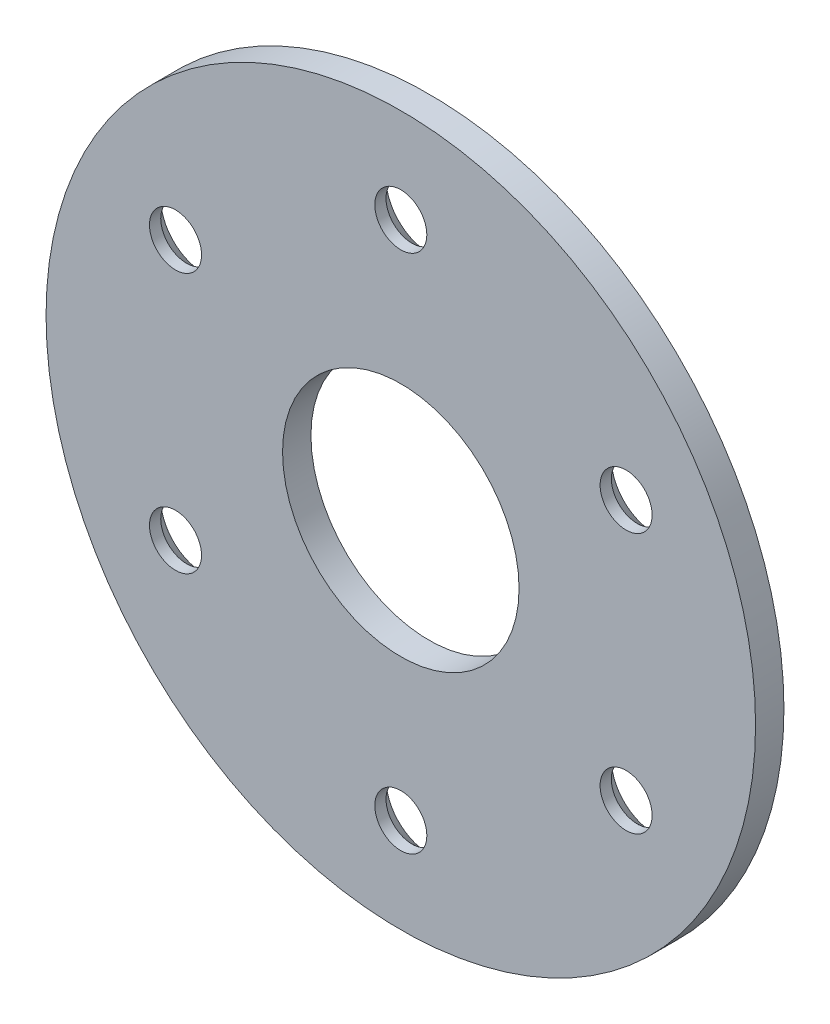
SolidWorks part; units mm, degrees
material "AISI 304"
ref_plane "Спереди" through (0, 0, 0) normal (0, 0, 1) x (1, 0, 0)
ref_plane "Сверху" through (0, 0, 0) normal (0, 1, 0) x (1, 0, 0)
ref_plane "Справа" through (0, 0, 0) normal (1, 0, 0) x (0, 0, -1)
sketch "Эскиз1" plane through (0, 0, 0) normal (0, 0, 1) x (1, 0, 0)
  circle A0 centre (0, 0) radius 75
  circle A1 centre (0, 0) radius 25
  circle A2 centre (0, 0) radius 55 construction
  circle A3 centre (0, 55) radius 5.5
  circle A4 centre (47.6314, 27.5) radius 5.5
  circle A5 centre (47.6314, -27.5) radius 5.5
  circle A6 centre (0, -55) radius 5.5
  circle A7 centre (-47.6314, -27.5) radius 5.5
  circle A8 centre (-47.6314, 27.5) radius 5.5
  point P19 (0, 0)
  dimension "D1" = 50
  dimension "D2" = 150
  dimension "D3" = 110
  dimension "D4" = 11
  dimension "D5" = 6
extrude "Бобышка-Вытянуть1" add sketch "Эскиз1" along normal mid plane 6
hole_wizard "Зенковка для винта с потайной головкой и внутренним шестигранником M81" positions "Эскиз4" profile "Эскиз5" countersink size "M8" standard "DIN"
sketch "Эскиз4" plane through (0, 0, -3) normal (0, 0, -1) x (-1, 0, 0)
  point P0 (0, 55)
  point P3 (47.6314, 27.5)
  point P6 (47.6314, -27.5)
  point P9 (0, -55)
  point P12 (-47.6314, -27.5)
  point P15 (-47.6314, 27.5)
sketch "Эскиз5" plane through (0, 55, -3) normal (1, 0, 0) x (0, 1, 0)
  line L0 (0, 0) -> (0, 19.7039)
  line L1 (0, 19.7039) -> (4.5, 17)
  line L2 (4.5, 17) -> (4.5, 4.625)
  line L3 (4.5, 4.625) -> (9.125, 0)
  line L5 (9.125, 0) -> (0, 0)
  line L6 (-4.5, 4.625) -> (-9.125, 0) construction
  line L10 (0, 19.7039) -> (-4.5, 17) construction
  line L11 (0, -6.35) -> (0, 107.95) construction
  dimension "Диаметр отверстия" = 9
  dimension "Глубина отверстия" = 17
  dimension "Диаметр передней зенковки" = 18.25
  dimension "Угол передней зенковки" = 90
  dimension "Угол заточки сверла" = 118
